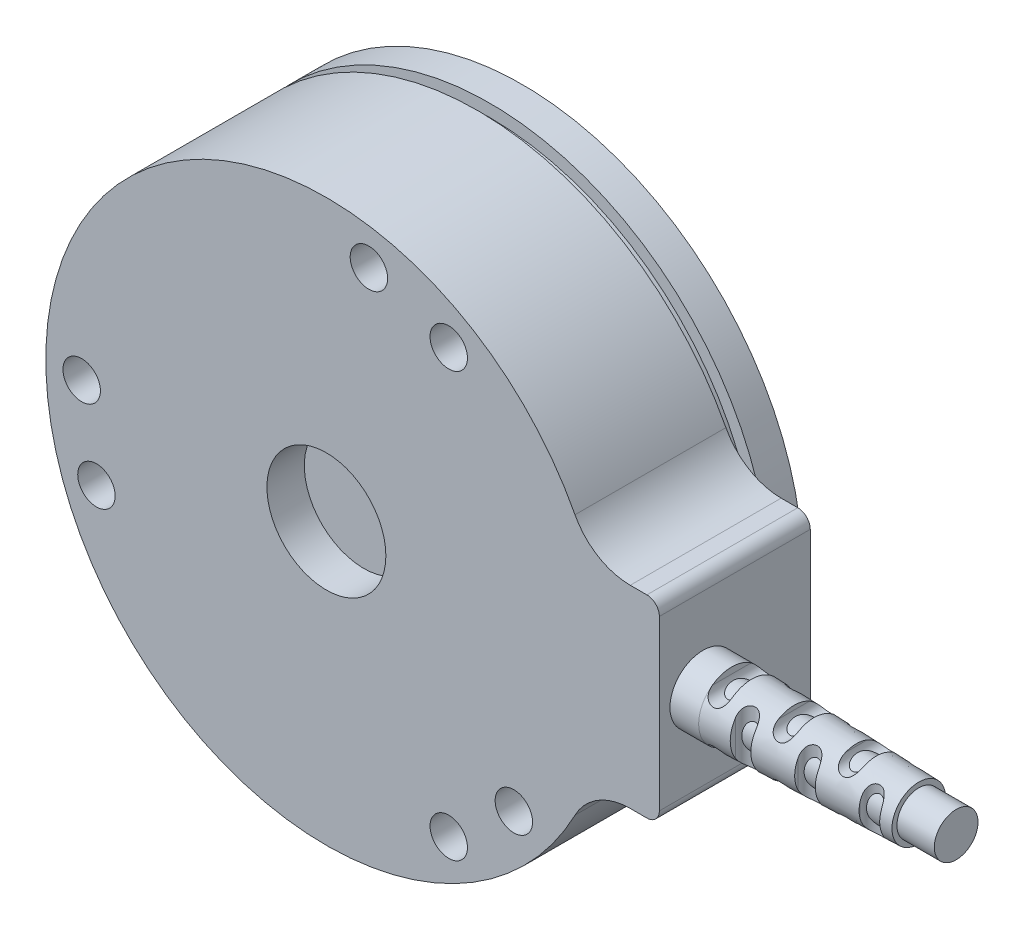
SolidWorks part; units mm, degrees
ref_plane "Piano frontale" through (0, 0, 0) normal (0, 0, 1) x (1, 0, 0)
ref_plane "Piano superiore" through (0, 0, 0) normal (0, 1, 0) x (1, 0, 0)
ref_plane "Piano destro" through (0, 0, 0) normal (1, 0, 0) x (0, 0, -1)
sketch "Schizzo1" plane through (0, 0, 0) normal (0, 0, 1) x (1, 0, 0)
  line L0 (0, 33.4226) -> (0, -33.5599) construction
  line L1 (-26.436, 0) -> (79.836, 0) construction
  line L2 (26.7, 6.75) -> (26.7, -6.75)
  line L3 (25.7, 7.75) -> (24.3657, 7.75)
  line L4 (25.7, -7.75) -> (24.3657, -7.75)
  line L5 (-39.3333, 14.3161) -> (50.0827, -18.2286) construction
  line L6 (12.1645, 33.4218) -> (-12.2682, -33.7066) construction
  line L7 (0, 0) -> (9.811, 16.9932) construction
  arc A0 (19.9356, 10.4318) -> (19.9356, -10.4318) centre (0, 0) ccw
  arc A1 (26.7, 6.75) -> (25.7, 7.75) centre (25.7, 6.75) ccw
  arc A2 (26.7, -6.75) -> (25.7, -7.75) centre (25.7, -6.75) cw
  arc A3 (24.3657, -7.75) -> (19.9356, -10.4318) centre (24.3657, -12.75) ccw
  arc A4 (24.3657, 7.75) -> (19.9356, 10.4318) centre (24.3657, 12.75) cw
  circle A5 centre (0, 0) radius 19.622 construction
  circle A6 centre (9.811, 16.9932) radius 1.5
  circle A7 centre (3.4073, 19.3239) radius 1.5
  circle A8 centre (15.0313, -12.6128) radius 1.5
  circle A9 centre (9.811, -16.9932) radius 1.5
  circle A10 centre (-18.4386, -6.7111) radius 1.5
  circle A11 centre (-19.622, 0) radius 1.5
  point P9 (26.7, 0)
  point P13 (26.7, 7.75)
  point P16 (26.7, -7.75)
  point P41 (0, 0)
  point P42 (0, 0)
  dimension "D1" = 45
  dimension "D4" = 1
  dimension "D5" = 5
  dimension "D7" = 39.244
  dimension "D8" = 3
  dimension "D2" = 15.5
  dimension "D3" = 26.7
  dimension "D6" = 20
  dimension "D9" = 10
  dimension "D10" = 3
extrude "Estrusione-Estrusione1" add sketch "Schizzo1" along normal blind 5
sketch "Schizzo2" plane through (0, 0, 5) normal (0, 0, 1) x (1, 0, 0)
  circle A0 centre (0, 0) radius 4.769
  dimension "D1" = 9.538
extrude "Taglio-Estrusione1" cut sketch "Schizzo2" against normal blind 3
sketch "Schizzo3" plane through (0, 0, 0) normal (0, 0, -1) x (-1, 0, 0)
  line L3 (-26.7, 6.75) -> (-26.7, -6.75)
  line L4 (-25.7, -7.75) -> (-24.3657, -7.75)
  line L5 (-24.3657, 7.75) -> (-25.7, 7.75)
  line L6 (-26.7, 6.75) -> (-26.7, -6.75)
  line L7 (-25.7, -7.75) -> (-24.3657, -7.75)
  line L8 (-24.3657, 7.75) -> (-25.7, 7.75)
  arc A5 (-25.7, 7.75) -> (-26.7, 6.75) centre (-25.7, 6.75) ccw
  arc A6 (-26.7, -6.75) -> (-25.7, -7.75) centre (-25.7, -6.75) ccw
  arc A7 (-19.9356, -10.4318) -> (-24.3657, -7.75) centre (-24.3657, -12.75) ccw
  arc A8 (-19.9356, -10.4318) -> (-19.9356, 10.4318) centre (0, 0) ccw
  arc A9 (-24.3657, 7.75) -> (-19.9356, 10.4318) centre (-24.3657, 12.75) ccw
  arc A10 (-25.7, 7.75) -> (-26.7, 6.75) centre (-25.7, 6.75) ccw
  arc A11 (-26.7, -6.75) -> (-25.7, -7.75) centre (-25.7, -6.75) ccw
  arc A12 (-19.9356, -10.4318) -> (-24.3657, -7.75) centre (-24.3657, -12.75) ccw
  arc A13 (-19.9356, -10.4318) -> (-19.9356, 10.4318) centre (0, 0) ccw
  arc A14 (-24.3657, 7.75) -> (-19.9356, 10.4318) centre (-24.3657, 12.75) ccw
  dimension "D1" = 0
extrude "Estrusione-Estrusione2" add sketch "Schizzo3" along normal blind 7.1
sketch "Schizzo4" plane through (0, 0, -7.1) normal (0, 0, -1) x (-1, 0, 0)
  circle A0 centre (0, 0) radius 21.5
  dimension "D1" = 43
extrude "Estrusione-Estrusione3" add sketch "Schizzo4" along normal blind 1 contours A0
sketch "Schizzo5" plane through (0, 0, -8.1) normal (0, 0, -1) x (-1, 0, 0)
  circle A0 centre (0, 0) radius 22.5
  dimension "D1" = 45
extrude "Estrusione-Estrusione4" add sketch "Schizzo5" along normal blind 2.6
sketch "Schizzo6" plane through (26.7, 0, 0) normal (1, 0, 0) x (0, 0, -1)
  line L0 (-5, -6.75) -> (-5, 6.75) construction
  circle A0 centre (-1.5, 0) radius 2.65
  dimension "D1" = 5.3
  dimension "D2" = 3.5
extrude "Estrusione-Estrusione5" add sketch "Schizzo6" along normal blind 17.3
chamfer "Smusso1" distance 15 distance2 0.5 1 edges at (44, 0, -1.15)
sketch "Schizzo7" plane through (0, 0, 5) normal (0, 0, 1) x (1, 0, 0)
  line L0 (26.7, 0) -> (44, 0) construction
  line L1 (26.7, -6.75) -> (26.7, 6.75) construction
  line L2 (44, -2.15) -> (44, 2.15) construction
  line L3 (29, 2.65) -> (44, 2.65) construction
  line L5 (29.8, 2.15) -> (29.8, 3.15) construction
  line L6 (29, 2.15) -> (29, 3.15)
  line L7 (30.6, 2.15) -> (30.6, 3.15)
  line L8 (29, -2.65) -> (29, 2.65) construction
  line L9 (34.8, 2.15) -> (34.8, 3.15) construction
  line L10 (34, 2.15) -> (34, 3.15)
  line L11 (35.6, 2.15) -> (35.6, 3.15)
  line L12 (39.8, 2.15) -> (39.8, 3.15) construction
  line L13 (39, 2.15) -> (39, 3.15)
  line L14 (40.6, 2.15) -> (40.6, 3.15)
  line L15 (29, -2.65) -> (44, -2.65) construction
  line L16 (39.8, -2.15) -> (39.8, -3.15) construction
  line L17 (39, -2.15) -> (39, -3.15)
  line L18 (40.6, -2.15) -> (40.6, -3.15)
  line L19 (34.8, -2.15) -> (34.8, -3.15) construction
  line L20 (34, -2.15) -> (34, -3.15)
  line L21 (35.6, -2.15) -> (35.6, -3.15)
  line L22 (29.8, -2.15) -> (29.8, -3.15) construction
  line L23 (29, -2.15) -> (29, -3.15)
  line L24 (30.6, -2.15) -> (30.6, -3.15)
  arc A0 (29, 2.15) -> (30.6, 2.15) centre (29.8, 2.15) ccw
  arc A1 (30.6, 3.15) -> (29, 3.15) centre (29.8, 3.15) ccw
  arc A2 (34, 2.15) -> (35.6, 2.15) centre (34.8, 2.15) ccw
  arc A3 (35.6, 3.15) -> (34, 3.15) centre (34.8, 3.15) ccw
  arc A4 (39, 2.15) -> (40.6, 2.15) centre (39.8, 2.15) ccw
  arc A5 (40.6, 3.15) -> (39, 3.15) centre (39.8, 3.15) ccw
  arc A6 (39, -2.15) -> (40.6, -2.15) centre (39.8, -2.15) cw
  arc A7 (40.6, -3.15) -> (39, -3.15) centre (39.8, -3.15) cw
  arc A8 (34, -2.15) -> (35.6, -2.15) centre (34.8, -2.15) cw
  arc A9 (35.6, -3.15) -> (34, -3.15) centre (34.8, -3.15) cw
  arc A10 (29, -2.15) -> (30.6, -2.15) centre (29.8, -2.15) cw
  arc A11 (30.6, -3.15) -> (29, -3.15) centre (29.8, -3.15) cw
  point P10 (29.8, 2.65)
  point P16 (29.8, 3.95)
  point P22 (34.8, 2.65)
  point P29 (39.8, 2.65)
  point P37 (39.8, -2.65)
  point P44 (34.8, -2.65)
  point P51 (29.8, -2.65)
  dimension "D1" = 0.8
  dimension "D2" = 1
  dimension "D3" = 3
extrude "Taglio-Estrusione2" cut sketch "Schizzo7" against normal through all
sketch "Schizzo8" plane through (0, 7.75, 0) normal (0, 1, 0) x (1, 0, 0)
  line L0 (29, -1.5) -> (44, -1.5) construction
  line L1 (29, -3.0492) -> (29, 0.0492) construction
  line L2 (44, -3.65) -> (44, 0.65) construction
  line L3 (29, 1.15) -> (44, 1.15) construction
  line L4 (32.25, 0.65) -> (32.25, 1.65) construction
  line L5 (31.45, 0.65) -> (31.45, 1.65)
  line L6 (33.05, 0.65) -> (33.05, 1.65)
  line L7 (29, 1.15) -> (29, 0.0492) construction
  line L8 (37.25, 0.65) -> (37.25, 1.65) construction
  line L9 (36.45, 0.65) -> (36.45, 1.65)
  line L10 (38.05, 0.65) -> (38.05, 1.65)
  line L11 (42.25, 0.65) -> (42.25, 1.65) construction
  line L12 (41.45, 0.65) -> (41.45, 1.65)
  line L13 (43.05, 0.65) -> (43.05, 1.65)
  line L14 (42.25, -3.65) -> (42.25, -4.65) construction
  line L15 (41.45, -3.65) -> (41.45, -4.65)
  line L16 (43.05, -3.65) -> (43.05, -4.65)
  line L17 (37.25, -3.65) -> (37.25, -4.65) construction
  line L18 (36.45, -3.65) -> (36.45, -4.65)
  line L19 (38.05, -3.65) -> (38.05, -4.65)
  line L20 (32.25, -3.65) -> (32.25, -4.65) construction
  line L21 (31.45, -3.65) -> (31.45, -4.65)
  line L22 (33.05, -3.65) -> (33.05, -4.65)
  arc A0 (31.45, 0.65) -> (33.05, 0.65) centre (32.25, 0.65) ccw
  arc A1 (33.05, 1.65) -> (31.45, 1.65) centre (32.25, 1.65) ccw
  arc A2 (36.45, 0.65) -> (38.05, 0.65) centre (37.25, 0.65) ccw
  arc A3 (38.05, 1.65) -> (36.45, 1.65) centre (37.25, 1.65) ccw
  arc A4 (41.45, 0.65) -> (43.05, 0.65) centre (42.25, 0.65) ccw
  arc A5 (43.05, 1.65) -> (41.45, 1.65) centre (42.25, 1.65) ccw
  arc A6 (41.45, -3.65) -> (43.05, -3.65) centre (42.25, -3.65) cw
  arc A7 (43.05, -4.65) -> (41.45, -4.65) centre (42.25, -4.65) cw
  arc A8 (36.45, -3.65) -> (38.05, -3.65) centre (37.25, -3.65) cw
  arc A9 (38.05, -4.65) -> (36.45, -4.65) centre (37.25, -4.65) cw
  arc A10 (31.45, -3.65) -> (33.05, -3.65) centre (32.25, -3.65) cw
  arc A11 (33.05, -4.65) -> (31.45, -4.65) centre (32.25, -4.65) cw
  point P11 (32.25, 1.15)
  point P21 (37.25, 1.15)
  point P28 (42.25, 1.15)
  point P34 (42.25, -4.15)
  point P41 (37.25, -4.15)
  point P48 (32.25, -4.15)
  dimension "D2" = 0.8
  dimension "D1" = 1
  dimension "D3" = 3.25
  dimension "D4" = 3
extrude "Taglio-Estrusione3" cut sketch "Schizzo8" against normal through all
sketch "Schizzo9" plane through (44, 0, 0) normal (1, 0, 0) x (0, 0, -1)
  circle A0 centre (-1.5, 0) radius 1.75
  dimension "D1" = 3.5
extrude "Estrusione-Estrusione6" add sketch "Schizzo9" along normal blind 3 and the other way blind 17.3
sketch "Schizzo10" plane through (0, 0, -10.7) normal (0, 0, -1) x (-1, 0, 0)
  line L0 (0, 0) -> (-59.7579, 0) construction
  line L1 (-57.3086, 20.8586) -> (57.3086, -20.8586) construction
  line L2 (14.6805, 40.3343) -> (-14.6805, -40.3343) construction
  line L3 (13.8858, -2.4484) -> (0, 0) construction
  line L4 (12.211, 7.05) -> (0, 0) construction
  circle A0 centre (0, 0) radius 14.1 construction
  circle A1 centre (13.8858, -2.4484) radius 1.5
  circle A2 centre (12.211, 7.05) radius 1.5
  circle A3 centre (0, -14.1) radius 1.5
  circle A4 centre (-9.0633, -10.8012) radius 1.5
  circle A5 centre (-12.211, 7.05) radius 1.5
  circle A6 centre (-4.8225, 13.2497) radius 1.5
  circle A7 centre (0, 0) radius 4.788
  point P22 (0, 0)
  dimension "D2" = 28.2
  dimension "D3" = 3
  dimension "D4" = 3
  dimension "D8" = 9.576
  dimension "D1" = 20
  dimension "D5" = 10
  dimension "D6" = 40
  dimension "D7" = 3
extrude "Taglio-Estrusione4" cut sketch "Schizzo10" against normal blind 3
